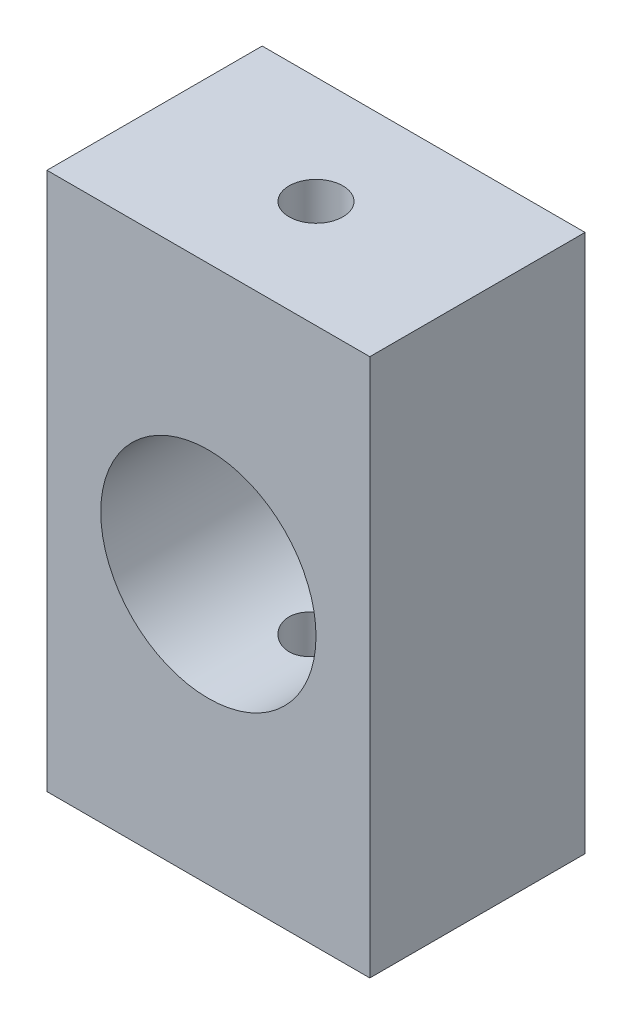
SolidWorks part; units mm, degrees
ref_plane "Ön Düzlem" through (0, 0, 0) normal (0, 0, 1) x (1, 0, 0)
ref_plane "Üst Düzlem" through (0, 0, 0) normal (0, 1, 0) x (1, 0, 0)
ref_plane "Sağ Düzlem" through (0, 0, 0) normal (1, 0, 0) x (0, 0, -1)
sketch "Çizim1" plane through (0, 0, 0) normal (0, 0, 1) x (1, 0, 0)
  line L1 (-15, 25) -> (15, 25)
  line L2 (-15, 25) -> (-15, -25)
  line L3 (-15, -25) -> (15, -25)
  line L4 (15, 25) -> (15, -25)
  circle A0 centre (0, 0) radius 10
  dimension "D5" = 20
  dimension "D1" = 50
  dimension "D2" = 30
  dimension "D3" = 15
  dimension "D4" = 25
extrude "Yükseklik-Ekstrüzyon1" add sketch "Çizim1" along normal blind 20
sketch "Çizim2" plane through (0, 25, 0) normal (0, 1, 0) x (1, 0, 0)
  line L0 (15, 0) -> (-15, 0) construction
  line L1 (-15, -20) -> (-15, 0) construction
  circle A0 centre (0, -10) radius 2.5
  dimension "D1" = 5
  dimension "D2" = 10
  dimension "D3" = 15
extrude "Kes-Ekstrüzyon1" cut sketch "Çizim2" against normal up to surface (50 mm away) up to face at (0, -25, 10)
